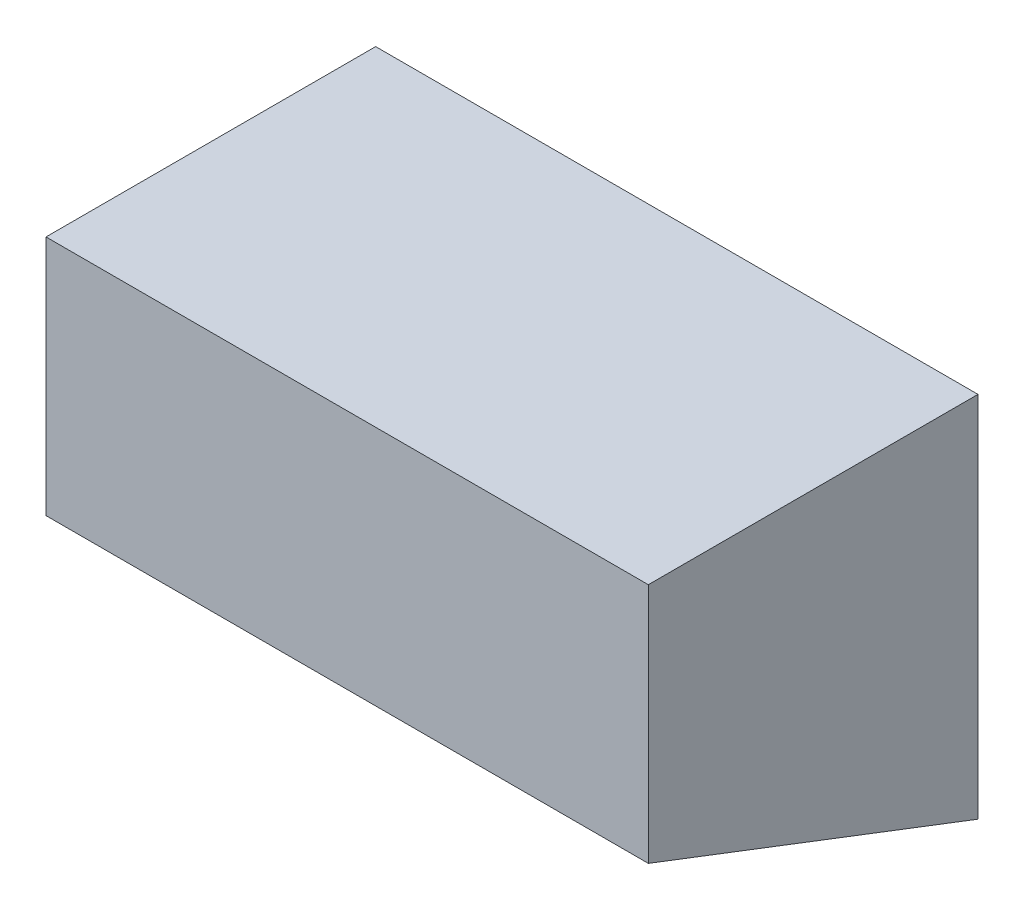
SolidWorks part; units mm, degrees
ref_plane "Front Plane" through (0, 0, 0) normal (0, 0, 1) x (1, 0, 0)
ref_plane "Top Plane" through (0, 0, 0) normal (0, 1, 0) x (1, 0, 0)
ref_plane "Right Plane" through (0, 0, 0) normal (1, 0, 0) x (0, 0, -1)
sketch "Sketch1" plane through (0, 0, 0) normal (1, 0, 0) x (0, 0, -1)
  line L0 (0, 0) -> (-40.5, 15.5465)
  line L1 (-40.5, 15.5465) -> (-40.5, 45.2)
  line L2 (-40.5, 45.2) -> (0, 45.2)
  line L3 (0, 45.2) -> (0, 0)
  dimension "D1" = 40.5
  dimension "D2" = 45.2
  dimension "D3" = 69
  dimension "D4" = 29.6535
extrude "Boss-Extrude1" add sketch "Sketch1" along normal mid plane 74
